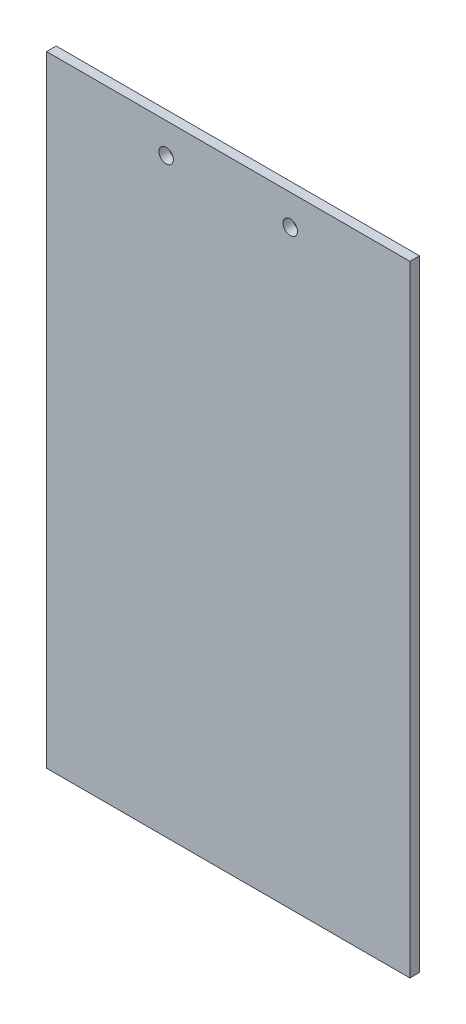
SolidWorks part; units mm, degrees
ref_plane "Alzado" through (0, 0, 0) normal (0, 0, 1) x (1, 0, 0)
ref_plane "Planta" through (0, 0, 0) normal (0, 1, 0) x (1, 0, 0)
ref_plane "Vista lateral" through (0, 0, 0) normal (1, 0, 0) x (0, 0, -1)
sketch "Croquis1" plane through (0, 0, 0) normal (0, 0, 1) x (1, 0, 0)
  line L1 (0, 0) -> (240, 0)
  line L2 (0, 0) -> (0, -410)
  line L3 (0, -410) -> (240, -410)
  line L4 (240, 0) -> (240, -410)
  dimension "D1" = 240
  dimension "D2" = 410
extrude "Saliente-Extruir1" add sketch "Croquis1" along normal blind 6.35
sketch "Croquis2" plane through (0, 0, 6.35) normal (0, 0, 1) x (1, 0, 0)
  line L0 (120, 0) -> (120, -20) construction
  line L1 (240, 0) -> (0, 0) construction
  line L2 (120, -20) -> (79, -20) construction
  line L3 (120, -20) -> (161, -20) construction
  line L4 (0, -410) -> (240, -410) construction
  circle A0 centre (161, -20) radius 4.7625
  circle A1 centre (79, -20) radius 4.7625
  dimension "D4" = 9.525
  dimension "D5" = 9.525
  dimension "D1" = 390
  dimension "D2" = 41
  dimension "D3" = 41
extrude "Cortar-Extruir1" cut sketch "Croquis2" against normal blind 10
